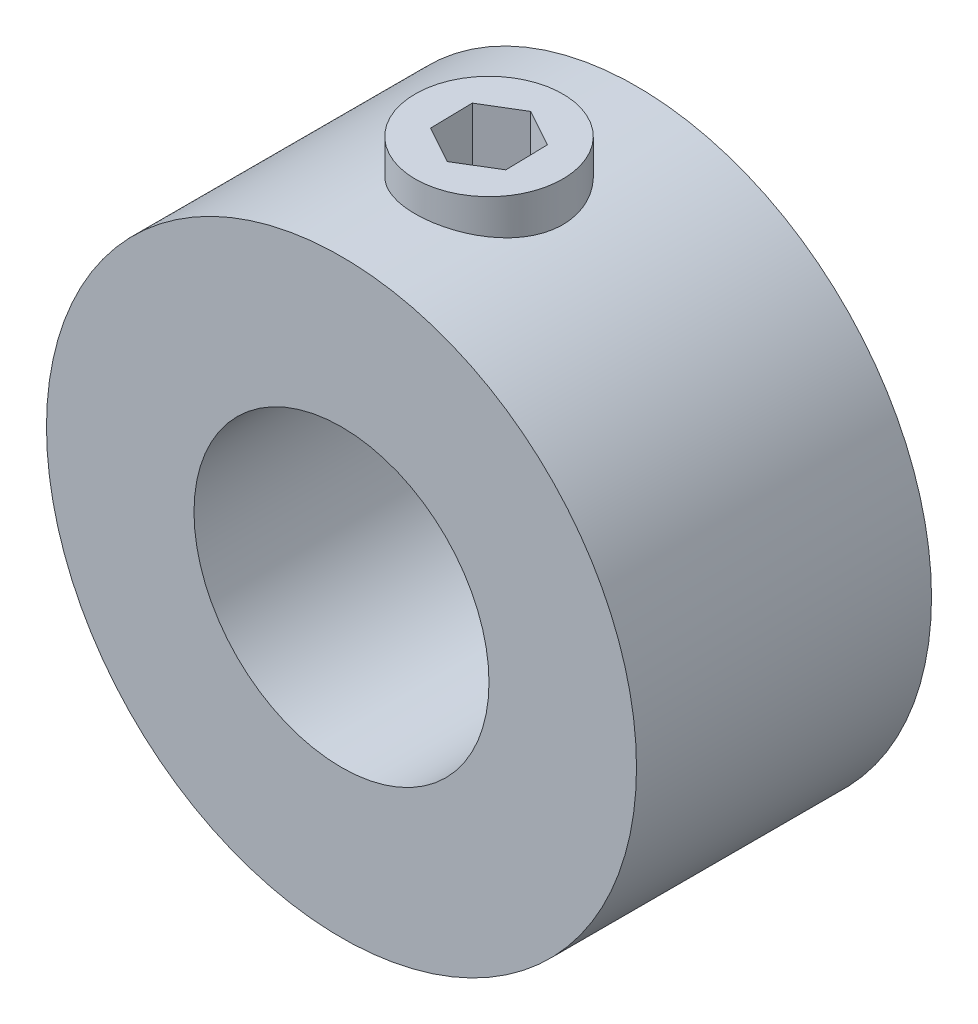
SolidWorks part; units mm, degrees
material "1023 Carbon Steel Sheet (SS)"
ref_plane "Front Plane" through (0, 0, 0) normal (0, 0, 1) x (1, 0, 0)
ref_plane "Top Plane" through (0, 0, 0) normal (0, 1, 0) x (1, 0, 0)
ref_plane "Right Plane" through (0, 0, 0) normal (1, 0, 0) x (0, 0, -1)
sketch "Sketch1" plane through (0, 0, 0) normal (0, 0, 1) x (1, 0, 0)
  circle A0 centre (0, 0) radius 3.175
  circle A1 centre (0, 0) radius 6.35
  dimension "Collar_ID" = 6.35
  dimension "Collar_OD" = 12.7
extrude "Body" add sketch "Sketch1" along normal blind 6.35
ref_plane "Plane1" through (0, 7, 0) normal (0, 1, 0) x (1, 0, 0)
sketch "Sketch2" plane through (0, 7, 0) normal (0, 1, 0) x (1, 0, 0)
  line L0 (3.175, 0) -> (-3.175, 0) construction
  line L1 (0, -3.4925) -> (0, 3.4925) construction
  circle A0 centre (0, -3.175) radius 1.5875
  dimension "D1" = 3.175
  dimension "D2" = 3.175
extrude "Set Screw" add sketch "Sketch2" against normal up to surface (0.65 mm away)
sketch "Sketch3" plane through (0, 7, 0) normal (0, 1, 0) x (1, 0, 0)
  line L1 (0.8027, -3.6174) -> (0.7845, -2.701)
  line L2 (0.7845, -2.701) -> (-0.0183, -2.2586)
  line L3 (-0.0183, -2.2586) -> (-0.8027, -2.7326)
  line L4 (-0.8027, -2.7326) -> (-0.7845, -3.649)
  line L5 (-0.7845, -3.649) -> (0.0183, -4.0914)
  line L6 (0.0183, -4.0914) -> (0.8027, -3.6174)
  circle A0 centre (0, -3.175) radius 0.7938 construction
  dimension "D1" = 1.5875
extrude "Hex Key" cut sketch "Sketch3" against normal blind 3
equation "\"D2@Sketch2\"=\"D1@Body\"/2"
